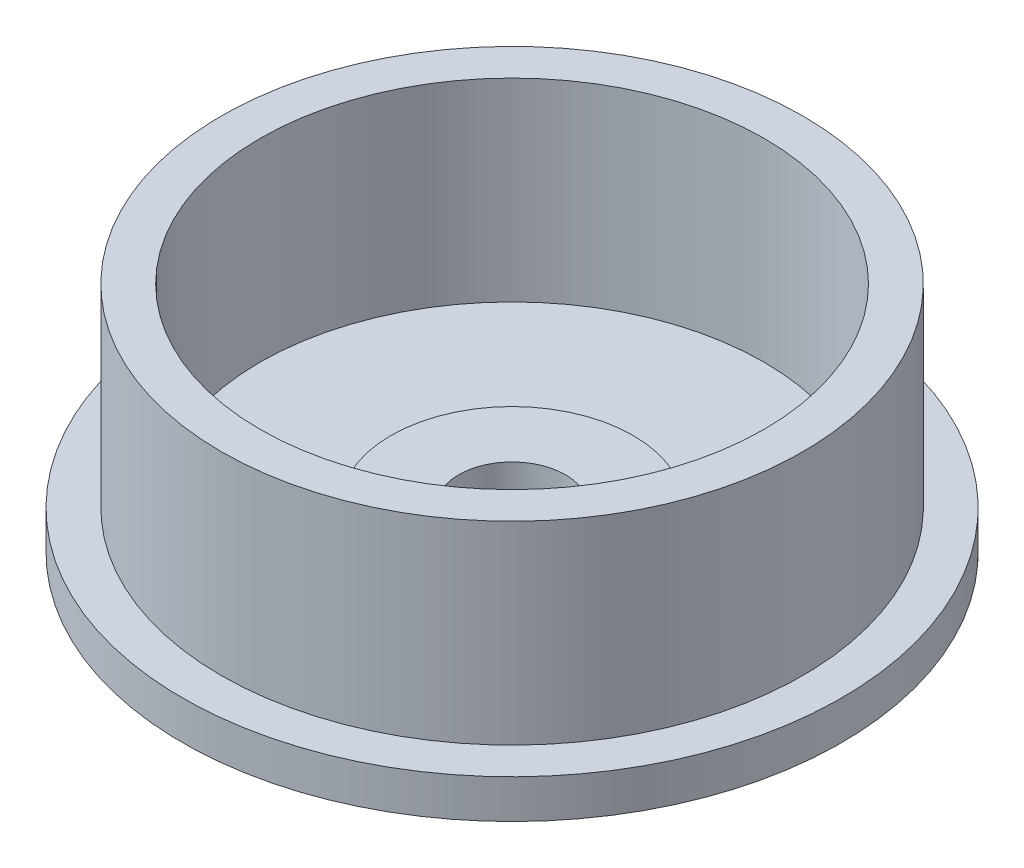
SolidWorks part; units mm, degrees
ref_plane "Front Plane" through (0, 0, 0) normal (0, 0, 1) x (1, 0, 0)
ref_plane "Top Plane" through (0, 0, 0) normal (0, 1, 0) x (1, 0, 0)
ref_plane "Right Plane" through (0, 0, 0) normal (1, 0, 0) x (0, 0, -1)
sketch "Sketch2" plane through (0, 0, 0) normal (0, 1, 0) x (1, 0, 0)
  circle A0 centre (0, 0) radius 15
  dimension "D2" = 30
extrude "Boss-Extrude1" add sketch "Sketch2" along normal blind 12
shell "Shell1" thickness 2
sketch "Sketch4" plane through (0, 0, 0) normal (0, -1, 0) x (1, 0, 0)
  circle A0 centre (0, 0) radius 2.75
  dimension "D1" = 5.5
extrude "Cut-Extrude1" cut sketch "Sketch4" against normal through all
sketch "Sketch5" plane through (0, 0, 0) normal (0, -1, 0) x (1, 0, 0)
  circle A0 centre (0, 0) radius 17
  circle A1 centre (0, 0) radius 15
  circle A2 centre (0, 0) radius 15
  dimension "D2" = 2
  dimension "D1" = 0
extrude "Boss-Extrude3" add sketch "Sketch5" against normal blind 2
sketch "Sketch7" plane through (0, 0, 0) normal (0, -1, 0) x (1, 0, 0)
  circle A0 centre (0, 0) radius 4.25
  circle A1 centre (0, 0) radius 2.75 construction
  circle A2 centre (0, 0) radius 2.75
  dimension "D1" = 1.5
extrude "Boss-Extrude5" add sketch "Sketch7" along normal blind 4.4
sketch "Sketch6" plane through (0, 2, 0) normal (0, 1, 0) x (1, 0, 0)
  circle A0 centre (0, 0) radius 2.75
  circle A1 centre (0, 0) radius 6.25
  circle A4 centre (0, 0) radius 2.75 construction
  dimension "D1" = 3.5
extrude "Boss-Extrude4" add sketch "Sketch6" along normal offset from surface (0.1 mm away) 6.5 up to face at (0, -4.4, -4.25)
